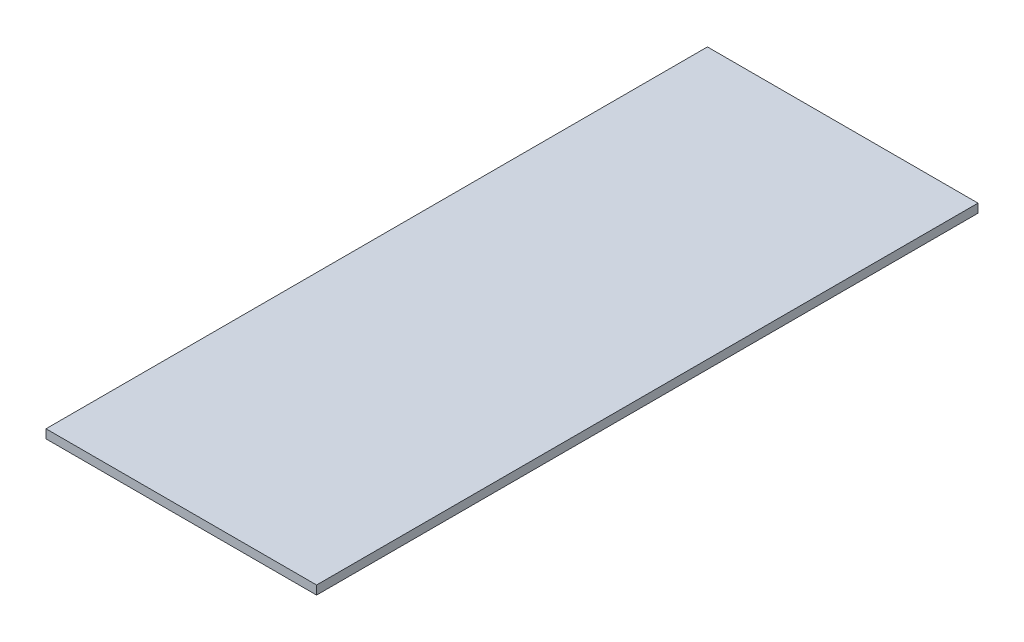
SolidWorks part; units mm, degrees
material "Pine"
ref_plane "Front Plane" through (0, 0, 0) normal (0, 0, 1) x (1, 0, 0)
ref_plane "Top Plane" through (0, 0, 0) normal (0, 1, 0) x (1, 0, 0)
ref_plane "Right Plane" through (0, 0, 0) normal (1, 0, 0) x (0, 0, -1)
sketch "Sketch1" plane through (0, 0, 0) normal (0, 1, 0) x (1, 0, 0)
  line L1 (-85.725, 209.55) -> (85.725, 209.55)
  line L2 (-85.725, 209.55) -> (-85.725, -209.55)
  line L3 (-85.725, -209.55) -> (85.725, -209.55)
  line L4 (85.725, 209.55) -> (85.725, -209.55)
  line L5 (-85.725, 209.55) -> (85.725, -209.55) construction
  line L6 (-85.725, -209.55) -> (85.725, 209.55) construction
  point P0 (0, 0)
  dimension "D1" = 171.45
  dimension "D2" = 419.1
extrude "Boss-Extrude1" add sketch "Sketch1" along normal blind 5.5562
